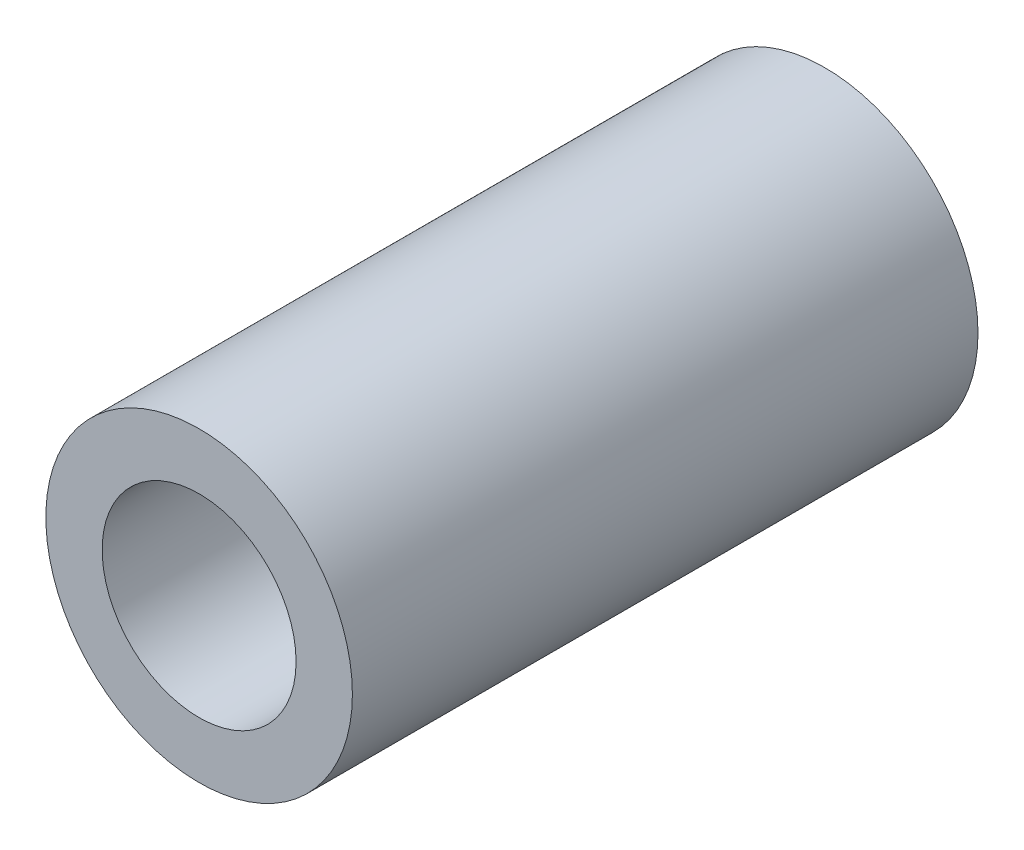
SolidWorks part; units mm, degrees
ref_plane "正面" through (0, 0, 0) normal (0, 0, 1) x (1, 0, 0)
ref_plane "平面" through (0, 0, 0) normal (0, 1, 0) x (1, 0, 0)
ref_plane "右側面" through (0, 0, 0) normal (1, 0, 0) x (0, 0, -1)
sketch "ｽｹｯﾁ1" plane through (0, 0, 0) normal (0, 0, 1) x (1, 0, 0)
  circle A0 centre (0, 0) radius 4.9
  circle A1 centre (0, 0) radius 3.1
  dimension "D1" = 9.8
  dimension "D2" = 6.2
extrude "ﾎﾞｽ - 押し出し1" add sketch "ｽｹｯﾁ1" along normal blind 20
